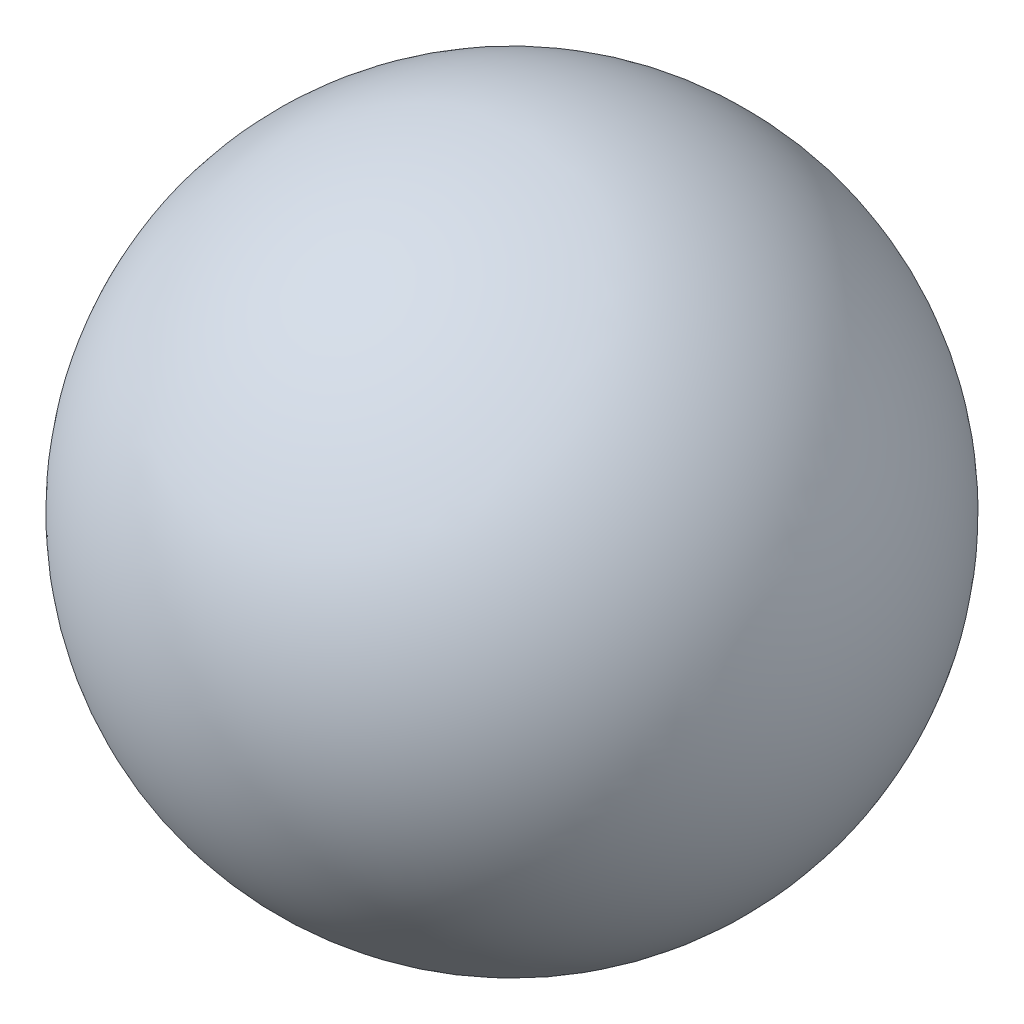
SolidWorks part; units mm, degrees
ref_plane "Front Plane" through (0, 0, 0) normal (0, 0, 1) x (1, 0, 0)
ref_plane "Top Plane" through (0, 0, 0) normal (0, 1, 0) x (1, 0, 0)
ref_plane "Right Plane" through (0, 0, 0) normal (1, 0, 0) x (0, 0, -1)
sketch "Sketch2" plane through (0, 0, 0) normal (0, 0, 1) x (1, 0, 0)
  line L0 (-139.7, 0) -> (139.7, 0)
  arc A0 (139.7, 0) -> (-139.7, 0) centre (0, 0) ccw
  dimension "D1" = 139.7
revolve "Revolve1" add sketch "Sketch2" angle 360 about L0
